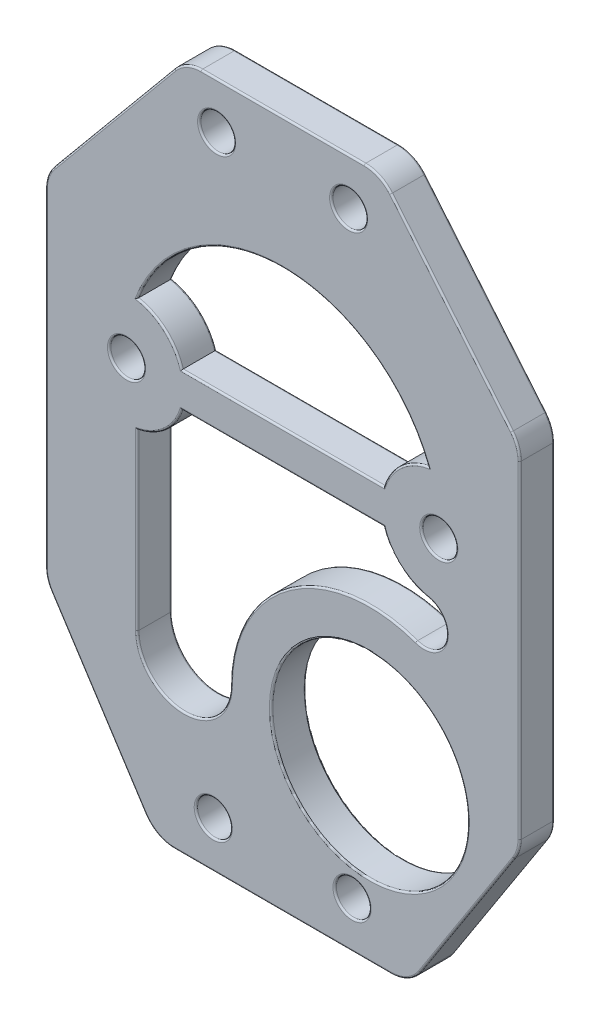
SolidWorks part; units mm, degrees
material "ABS"
ref_plane "Спереди" through (0, 0, 0) normal (0, 0, 1) x (1, 0, 0)
ref_plane "Сверху" through (0, 0, 0) normal (0, 1, 0) x (1, 0, 0)
ref_plane "Справа" through (0, 0, 0) normal (1, 0, 0) x (0, 0, -1)
sketch "Эскиз1" plane through (0, 0, 0) normal (0, 0, 1) x (1, 0, 0)
  line L0 (0, 0) -> (0, 59.5) construction
  line L1 (11, 0) -> (-11, 0)
  line L2 (-11, 0) -> (-20.5, 14.6969)
  line L3 (-20.5, 14.6969) -> (-20.5, 44.9969)
  line L4 (-20.5, 44.9969) -> (-8.4591, 59.5)
  line L5 (-8.4591, 59.5) -> (8.4591, 59.5)
  line L6 (20.5, 44.9969) -> (8.4591, 59.5)
  line L7 (20.5, 14.6969) -> (20.5, 44.9969)
  line L8 (11, 0) -> (20.5, 14.6969)
  line L9 (-13.5, 34.6969) -> (13.5, 34.6969) construction
  line L10 (-8.7303, 36.1969) -> (8.7303, 36.1969)
  line L11 (8.7303, 33.1969) -> (-8.7303, 33.1969) construction
  line L12 (8.7303, 33.1969) -> (8.7303, 36.1969) construction
  line L13 (8.7303, 36.1969) -> (-8.7303, 36.1969) construction
  line L14 (-8.7303, 33.1969) -> (-8.7303, 36.1969) construction
  line L15 (8.7303, 33.1969) -> (-8.7303, 36.1969) construction
  line L16 (8.7303, 36.1969) -> (-8.7303, 33.1969) construction
  line L17 (-8.7303, 33.1969) -> (8.7303, 33.1969)
  line L18 (13.5, 34.6969) -> (11.5456, 25.9944) construction
  line L19 (-12.5741, 29.7834) -> (-12.5741, 14.6969)
  circle A0 centre (-5.7091, 55.5) radius 1.5
  circle A1 centre (-13.5, 34.6969) radius 1.5
  circle A2 centre (-6, 4) radius 1.5
  circle A3 centre (6, 4) radius 1.5
  circle A4 centre (13.5, 34.6969) radius 1.5
  circle A5 centre (5.7091, 55.5) radius 1.5
  circle A6 centre (7.5, 14.6969) radius 8.5
  circle A7 centre (13.5, 34.6969) radius 5 construction
  circle A8 centre (-13.5, 34.6969) radius 5 construction
  circle A9 centre (7.5, 14.6969) radius 12 construction
  arc A10 (-12.5741, 39.6105) -> (12.5741, 39.6105) centre (0, 34.6969) cw
  arc A11 (-12.5741, 39.6105) -> (-8.7303, 36.1969) centre (-13.5, 34.6969) cw
  arc A12 (8.7303, 36.1969) -> (12.5741, 39.6105) centre (13.5, 34.6969) cw
  arc A13 (-8.7303, 33.1969) -> (-12.5741, 29.7834) centre (-13.5, 34.6969) cw
  arc A14 (8.7303, 33.1969) -> (12.5741, 29.7834) centre (13.5, 34.6969) ccw
  arc A15 (12.5741, 29.7834) -> (11.5456, 25.9944) centre (12.2094, 27.8483) cw
  arc A16 (11.5456, 25.9944) -> (-4.5, 14.6969) centre (7.5, 14.6969) ccw
  arc A17 (-12.5741, 14.6969) -> (-4.5, 14.6969) centre (-8.537, 14.6969) ccw
  point P44 (7.5, 15.2889)
  dimension "D2" = 3
  dimension "D14" = 17
  dimension "D19" = 13.5
  dimension "D1" = 59.5
  dimension "D3" = 6
  dimension "D4" = 4
  dimension "D5" = 11
  dimension "D6" = 17.5
  dimension "D7" = 30.3
  dimension "D8" = 7
  dimension "D9" = 10.3
  dimension "D10" = 2.75
  dimension "D11" = 4
  dimension "D12" = 18.85
  dimension "D13" = 20.5
  dimension "D15" = 13
  dimension "D20" = 3
  dimension "D16" = 3.5
  dimension "D17" = 3.5
  dimension "D18" = 3.5
extrude "Бобышка-Вытянуть1" add sketch "Эскиз1" along normal blind 3
fillet "Скругление1" radius 3 8 edges at (-20.5, 44.9969, 1.5) (-8.4591, 59.5, 1.5) (8.4591, 59.5, 1.5) (20.5, 44.9969, 1.5) (20.5, 14.6969, 1.5) (11, 0, 1.5) (-11, 0, 1.5) (-20.5, 14.6969, 1.5)
fillet "Скругление2" radius 0.15 68 edges at (0.5916, 24.5088, 0) (-8.537, 10.6599, 0) (-12.5741, 22.2402, 0) (-10.1799, 30.9584, 0) (0, 33.1969, 0) (10.1799, 30.9584, 0) (14.1098, 27.3325, 0) (4.2091, 55.5, 0) (4.5, 4, 0) (-4.5, 4, 0) (-4.2091, 55.5, 0) (-20.3774, 14.7331, 0) (-15.953, 7.6625, 0) (-10.8013, 0.3651, 0) (0, 0, 0) (10.8013, 0.3651, 0) (15.953, 7.6625, 0) (20.3774, 14.7331, 0) (20.5, 29.748, 0) (20.3217, 44.9326, 0) (14.5835, 52.1233, 0) (8.3256, 59.2156, 0) (0, 59.5, 0) (-8.3256, 59.2156, 0) (-14.5835, 52.1233, 0) (-20.3217, 44.9326, 0) (-20.5, 29.748, 0) (-12, 34.6969, 0) (16, 14.6969, 0) (10.1799, 38.4355, 0) (0, 36.1969, 0) (-10.1799, 38.4355, 0) (0, 48.1969, 0) (12, 34.6969, 0) (0, 33.1969, 3) (-10.1799, 30.9584, 3) (-12.5741, 22.2402, 3) (-8.537, 10.6599, 3) (0.5916, 24.5088, 3) (14.1098, 27.3325, 3) (10.1799, 30.9584, 3) (16, 14.6969, 3) (-4.5, 4, 3) (-12, 34.6969, 3) (-4.2091, 55.5, 3) (-8.3256, 59.2156, 3) (0, 59.5, 3) (8.3256, 59.2156, 3) (14.5835, 52.1233, 3) (20.3217, 44.9326, 3) (20.5, 29.748, 3) (20.3774, 14.7331, 3) (15.953, 7.6625, 3) (10.8013, 0.3651, 3) (0, 0, 3) (-10.8013, 0.3651, 3) (-15.953, 7.6625, 3) (-20.3774, 14.7331, 3) (-20.5, 29.748, 3) (-20.3217, 44.9326, 3) (-14.5835, 52.1233, 3) (0, 36.1969, 3) (10.1799, 38.4355, 3) (0, 48.1969, 3) (-10.1799, 38.4355, 3) (4.5, 4, 3) (12, 34.6969, 3) (4.2091, 55.5, 3)
scale "Масштаб1" scale about centroid uniform scaling yes scale factor 2.2
equation "\"Scale\"= 1"
